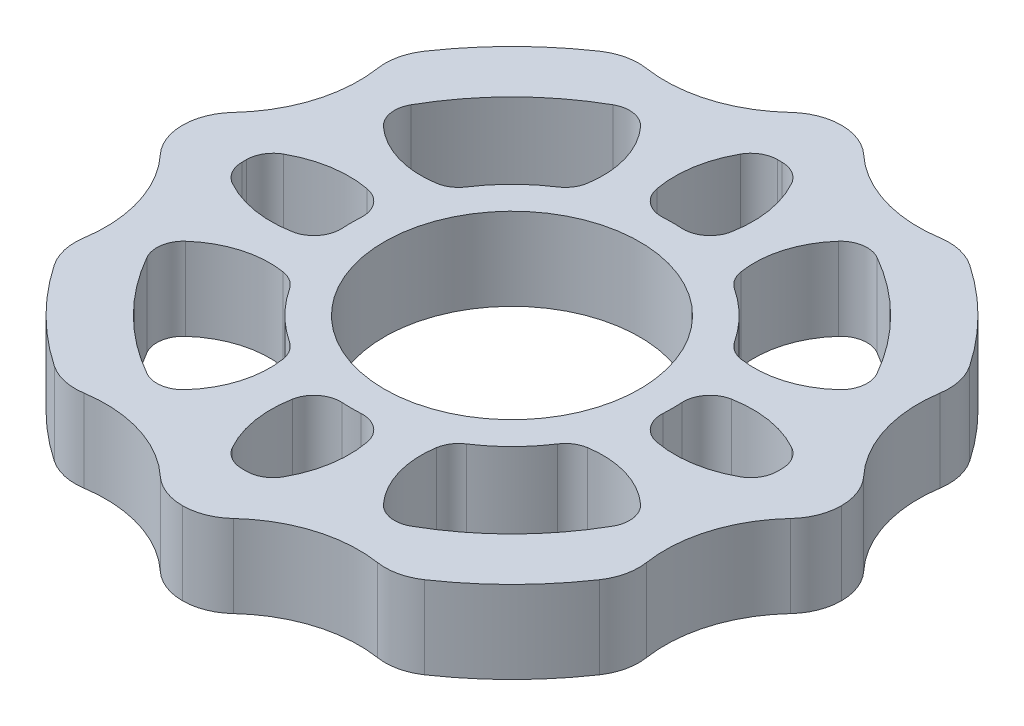
SolidWorks part; units mm, degrees
ref_plane "Ebene vorne" through (0, 0, 0) normal (0, 0, 1) x (1, 0, 0)
ref_plane "Ebene oben" through (0, 0, 0) normal (0, 1, 0) x (1, 0, 0)
ref_plane "Ebene rechts" through (0, 0, 0) normal (1, 0, 0) x (0, 0, -1)
sketch "Skizze1" plane through (0, 0, 0) normal (0, 1, 0) x (1, 0, 0)
  circle A0 centre (0, 0) radius 8
  circle A1 centre (0, 0) radius 3.1
  dimension "D1" = 16
  dimension "D2" = 6.2
extrude "Aufsatz-Linear austragen1" add sketch "Skizze1" along normal blind 2
sketch "Skizze2" plane through (0, 2, 0) normal (0, 1, 0) x (1, 0, 0)
  arc A0 (0.4094, 6.4871) -> (-0.4094, 6.4871) centre (0, 0) ccw
  arc A1 (0.7209, 3.8328) -> (-0.7209, 3.8328) centre (0, 0) ccw
  arc A2 (0.7209, 3.8328) -> (0.4094, 6.4871) centre (-1.65, 4.9) ccw
  arc A3 (-0.4094, 6.4871) -> (-0.7209, 3.8328) centre (1.65, 4.9) ccw
  point P1 (0, 0)
  point P8 (0, 0)
  point P10 (0.5334, 3.8631)
  point P11 (0.5334, 3.8634)
  point P12 (0, 0)
  point P14 (1.5377, 4.9625)
  dimension "D1" = 13
  dimension "D2" = 7.8
  dimension "D3" = 2.6
  dimension "D4" = 4.9
  dimension "D5" = 3.3
extrude "Schnitt-Linear austragen1" cut sketch "Skizze2" against normal through all
sketch "Skizze3" plane through (0, 2, 0) normal (0, 1, 0) x (1, 0, 0)
  line L0 (0, 0) -> (0, 8) construction
  line L1 (0, 0) -> (5.6569, 5.6569) construction
  arc A0 (3.3861, 1.9351) -> (1.9351, 3.3861) centre (0, 0) ccw
  arc A1 (5.868, 2.7958) -> (2.7958, 5.868) centre (0, 0) ccw
  circle A2 centre (0, 0) radius 8 construction
  arc A3 (2.7958, 5.868) -> (1.9351, 3.3861) centre (4.0447, 4.0447) ccw
  arc A4 (3.3861, 1.9351) -> (5.868, 2.7958) centre (4.0447, 4.0447) ccw
  dimension "D1" = 45
  dimension "D2" = 4.42
  dimension "D3" = 5.72
extrude "Schnitt-Linear austragen2" cut sketch "Skizze3" against normal through all
sketch "Skizze4" plane through (0, 2, 0) normal (0, 1, 0) x (1, 0, 0)
  line L0 (-3.075, 10) -> (3.075, 10) construction
  line L1 (0, 10) -> (0, 0) construction
  arc A0 (-4.0023, 6.9269) -> (-0.5812, 7.9789) centre (-3.075, 10) ccw
  arc A1 (0.5812, 7.9789) -> (4.0023, 6.9269) centre (3.075, 10) ccw
  circle A2 centre (0, 0) radius 8 construction
  arc A3 (4.0023, 6.9269) -> (0.5812, 7.9789) centre (0, 0) ccw
  arc A4 (-0.5812, 7.9789) -> (-4.0023, 6.9269) centre (0, 0) ccw
  point P1 (0, 0)
  point P3 (0, 10.3267)
  point P6 (-3.075, 10.2605)
  dimension "D1" = 3.21
  dimension "D2" = 6.15
  dimension "D3" = 10
extrude "Schnitt-Linear austragen3" cut sketch "Skizze4" against normal through all
pattern_circular "Kreismuster1" count 4 over 360 about axis through (0, 0, 0) along (0, 1, 0) of "Schnitt-Linear austragen1", "Schnitt-Linear austragen2", "Schnitt-Linear austragen3"
fillet "Verrundung2" radius 0.65 32 edges at (-2.7958, 1, -5.868) (-1.9351, 1, -3.3861) (-3.3861, 1, -1.9351) (-5.868, 1, -2.7958) (-5.868, 1, 2.7958) (-3.3861, 1, 1.9351) (-1.9351, 1, 3.3861) (-2.7958, 1, 5.868) (2.7958, 1, 5.868) (1.9351, 1, 3.3861) (3.3861, 1, 1.9351) (5.868, 1, 2.7958) (-6.4871, 1, -0.4094) (-3.8328, 1, -0.7209) (-3.8328, 1, 0.7209) (-6.4871, 1, 0.4094) (-0.4094, 1, 6.4871) (-0.7209, 1, 3.8328) (0.7209, 1, 3.8328) (0.4094, 1, 6.4871) (6.4871, 1, 0.4094) (3.8328, 1, 0.7209) (3.8328, 1, -0.7209) (6.4871, 1, -0.4094) (5.868, 1, -2.7958) (3.3861, 1, -1.9351) (1.9351, 1, -3.3861) (0.4094, 1, -6.4871) (0.7209, 1, -3.8328) (-0.7209, 1, -3.8328) (-0.4094, 1, -6.4871) (2.7958, 1, -5.868)
fillet "Verrundung3" radius 1.3 16 edges at (4.0023, 1, -6.9269) (0.5812, 1, -7.9789) (-0.5812, 1, -7.9789) (-4.0023, 1, -6.9269) (-6.9269, 1, -4.0023) (-7.9789, 1, -0.5812) (-7.9789, 1, 0.5812) (-6.9269, 1, 4.0023) (-4.0023, 1, 6.9269) (-0.5812, 1, 7.9789) (0.5812, 1, 7.9789) (4.0023, 1, 6.9269) (6.9269, 1, 4.0023) (7.9789, 1, 0.5812) (7.9789, 1, -0.5812) (6.9269, 1, -4.0023)
